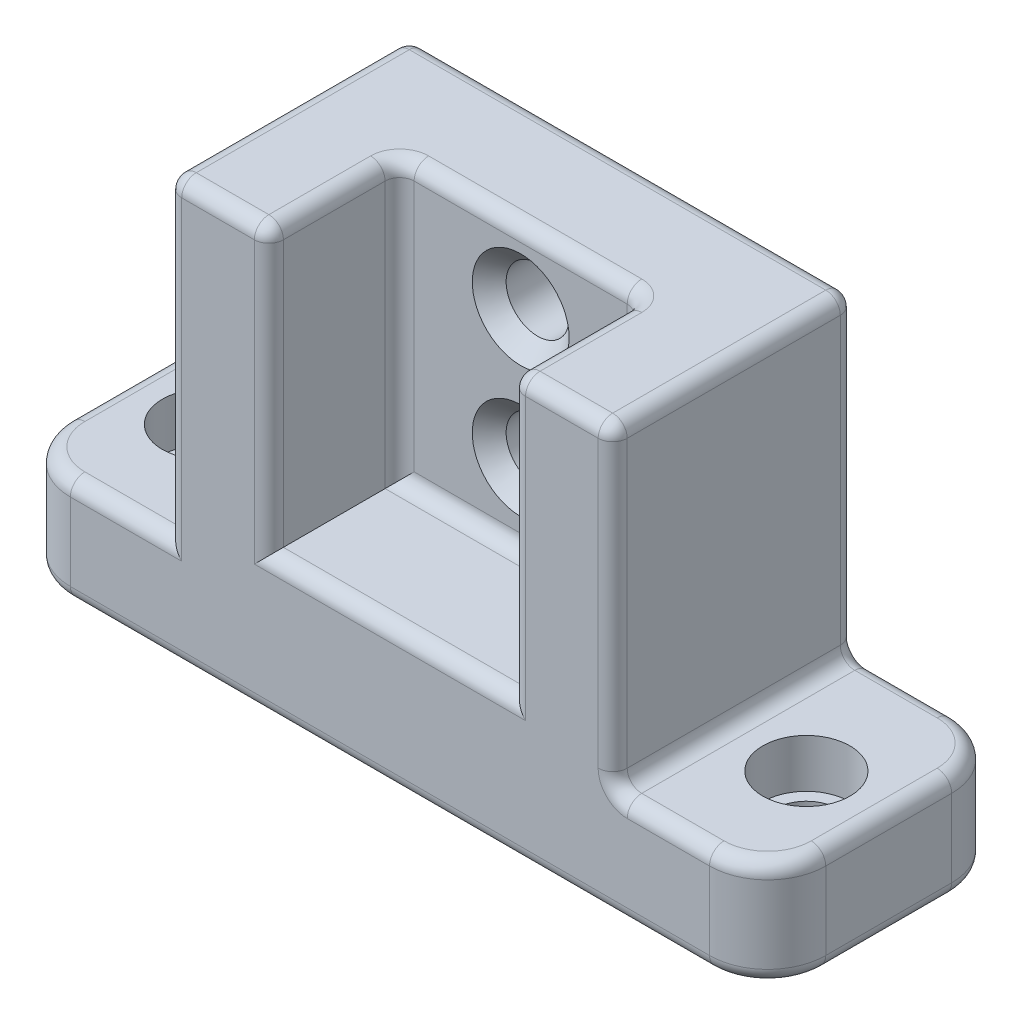
SolidWorks part; units mm, degrees
ref_plane "Front Plane" through (0, 0, 0) normal (0, 0, 1) x (1, 0, 0)
ref_plane "Top Plane" through (0, 0, 0) normal (0, 1, 0) x (1, 0, 0)
ref_plane "Right Plane" through (0, 0, 0) normal (1, 0, 0) x (0, 0, -1)
sketch "Sketch2" plane through (0, 0, 0) normal (0, 0, 1) x (1, 0, 0)
  line L1 (-46, -43.5) -> (46, -43.5)
  line L2 (-46, -43.5) -> (-46, 43.5)
  line L3 (-46, 43.5) -> (46, 43.5)
  line L4 (46, -43.5) -> (46, 43.5)
  line L5 (-46, -43.5) -> (46, 43.5) construction
  line L6 (-46, 43.5) -> (46, -43.5) construction
  point P0 (0, 0)
  dimension "D1" = 92
  dimension "D2" = 87
extrude "Boss-Extrude1" add sketch "Sketch2" along normal blind 50
sketch "Sketch4" plane through (0, 0, 50) normal (0, 0, 1) x (1, 0, 0)
  line L0 (46, 43.5) -> (-46, 43.5) construction
  line L1 (-25, 101.5) -> (25, 101.5)
  line L2 (-25, 101.5) -> (-25, -14.5)
  line L3 (-25, -14.5) -> (25, -14.5)
  line L4 (25, 101.5) -> (25, -14.5)
  line L5 (-25, 101.5) -> (25, -14.5) construction
  line L6 (-25, -14.5) -> (25, 101.5) construction
  point P0 (0, 43.5)
  dimension "D1" = 116
  dimension "D2" = 50
extrude "Cut-Extrude1" cut sketch "Sketch4" against normal blind 27 contours L2 L1 L4 L3
sketch "Sketch5" plane through (0, -43.5, 0) normal (0, -1, 0) x (1, 0, 0)
  line L0 (0, 0) -> (0, 50)
  line L1 (-46, 50) -> (46, 50) construction
  line L3 (-78, 0) -> (78, 0)
  line L4 (-78, 0) -> (-78, 50)
  line L5 (-78, 50) -> (78, 50)
  line L6 (78, 0) -> (78, 50)
  line L7 (-78, 0) -> (78, 50) construction
  line L8 (-78, 50) -> (78, 0) construction
  point P5 (0, 25)
  line M3 (46, 0) -> (46, 50)
  line M5 (-46, 50) -> (-46, 0)
  dimension "D1" = 156
extrude "Boss-Extrude2" add sketch "Sketch5" against normal blind 22 contours L3 L6 L5 M3 | L5 L4 L3 M5
fillet "Fillet1" radius 12 4 edges at (-78, -32.5, 50) (-78, -32.5, 0) (78, -32.5, 0) (78, -32.5, 50)
fillet "Fillet2" radius 3 37 edges at (0, -14.5, 50) (0, -14.5, 23) (-74.4853, -43.5, 3.5147) (-78, -43.5, 25) (-78, -21.5, 25) (-74.4853, -43.5, 46.4853) (0, -43.5, 50) (74.4853, -43.5, 46.4853) (78, -43.5, 25) (78, -21.5, 25) (74.4853, -43.5, 3.5147) (0, -43.5, 0) (46, 11, 0) (46, 11, 50) (46, -21.5, 25) (74.4853, -21.5, 3.5147) (56, -21.5, 0) (74.4853, -21.5, 46.4853) (56, -21.5, 50) (25, 14.5, 23) (25, 14.5, 50) (25, 43.5, 36.5) (46, 43.5, 25) (0, 43.5, 0) (0, 43.5, 23) (-25, 14.5, 50) (-25, 14.5, 23) (-25, 43.5, 36.5) (-35.5, 43.5, 50) (-46, 43.5, 25) (-46, 11, 50) (-46, 11, 0) (-56, -21.5, 0) (-74.4853, -21.5, 3.5147) (-74.4853, -21.5, 46.4853) (-56, -21.5, 50) (35.5, 43.5, 50)
sketch "Sketch6" plane through (0, -21.5, 0) normal (0, 1, 0) x (1, 0, 0)
  line L0 (25, -26) -> (-25, -26) construction
  line L1 (-78, -52) -> (78, -52)
  line L2 (-78, -52) -> (-78, 0)
  line L3 (-78, 0) -> (78, 0)
  line L4 (78, -52) -> (78, 0)
  line L5 (-78, -52) -> (78, 0) construction
  line L6 (-78, 0) -> (78, -52) construction
  point P0 (0, -26)
  dimension "D1" = 156
  dimension "D2" = 52
sketch "Sketch7" plane through (0, 0, 23) normal (0, 0, 1) x (1, 0, 0)
  line L0 (0, 43.5) -> (0, 28.5)
  line L1 (-22, 43.5) -> (22, 43.5) construction
  line L2 (0, 28.5) -> (0, 1.5)
  circle A0 centre (0, 28.5) radius 6.5
  circle A1 centre (0, 1.5) radius 6.5
  dimension "D2" = 13
  dimension "D4" = 13
  dimension "D1" = 15
  dimension "D3" = 27
extrude "Cut-Extrude2" cut sketch "Sketch7" against normal blind 70
chamfer "Chamfer2" distance 3.5 angle 45 2 edges at (6.5, 1.5, 23) (6.5, 28.5, 23)
sketch "Sketch9" plane through (0, -21.5, 0) normal (0, 1, 0) x (1, 0, 0)
  line L0 (-78, 0) -> (78, 0) construction
  line L1 (-62, -52) -> (62, -52)
  line L2 (-62, -52) -> (-62, 0)
  line L3 (-62, 0) -> (62, 0)
  line L4 (62, -52) -> (62, 0)
  line L5 (-62, -52) -> (62, 0) construction
  line L6 (-62, 0) -> (62, -52) construction
  circle A0 centre (-62, -26) radius 6.5
  circle A1 centre (62, -26) radius 6.5
  point P0 (0, -26)
  dimension "D2" = 13
  dimension "D3" = 13
  dimension "D1" = 124
extrude "Cut-Extrude3" cut sketch "Sketch9" against normal blind 57 contours L2 A0 | L2 A0 | L4 A1 | L4 A1
sketch "Sketch10" plane through (0, -21.5, 0) normal (0, 1, 0) x (1, 0, 0)
  circle A0 centre (-62, -26) radius 9
  circle A1 centre (62, -26) radius 9
  dimension "D1" = 18
  dimension "D2" = 18
extrude "Cut-Extrude4" cut sketch "Sketch10" against normal blind 10
